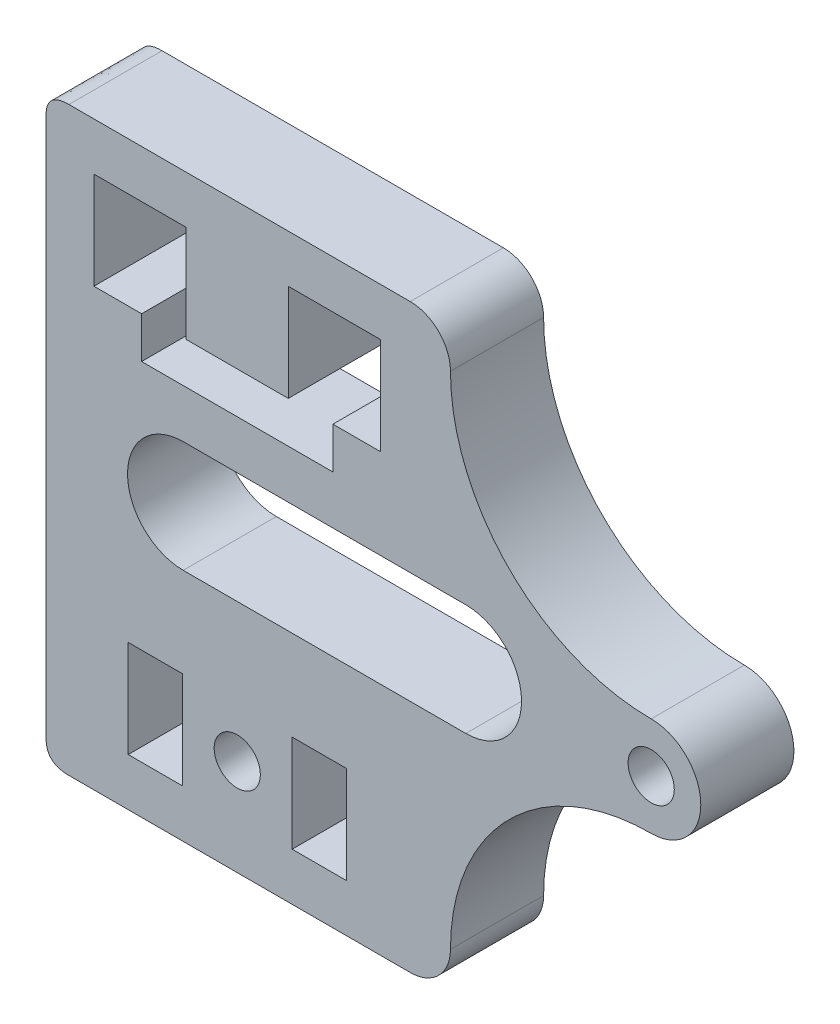
SolidWorks part; units mm, degrees
material "Acrylic (Medium-high impact)"
ref_plane "Front Plane" through (0, 0, 0) normal (0, 0, 1) x (1, 0, 0)
ref_plane "Top Plane" through (0, 0, 0) normal (0, 1, 0) x (1, 0, 0)
ref_plane "Right Plane" through (0, 0, 0) normal (1, 0, 0) x (0, 0, -1)
sketch "Sketch1" plane through (0, 0, 0) normal (0, 0, 1) x (1, 0, 0)
  line L0 (405.5669, 551.1889) -> (405.5669, 553.7889)
  line L1 (396.3551, 553.7889) -> (402.763, 553.7889)
  line L2 (393.5512, 553.7889) -> (393.5512, 551.1889)
  line L3 (393.5512, 551.1889) -> (405.5669, 551.1889)
  line L4 (390.5551, 559.8889) -> (390.5551, 553.7889)
  line L5 (393.5512, 553.7889) -> (390.5551, 553.7889)
  line L6 (396.3551, 559.8889) -> (390.5551, 559.8889)
  line L7 (396.3551, 553.7889) -> (396.3551, 559.8889)
  line L8 (405.5669, 553.7889) -> (408.563, 553.7889)
  line L9 (408.563, 553.7889) -> (408.563, 559.8889)
  line L10 (402.763, 559.8889) -> (402.763, 553.7889)
  line L11 (408.563, 559.8889) -> (402.763, 559.8889)
  line L12 (392.709, 535.4889) -> (392.709, 529.3889)
  line L13 (392.709, 529.3889) -> (396.109, 529.3889)
  line L14 (396.109, 535.4889) -> (392.709, 535.4889)
  line L15 (396.109, 529.3889) -> (396.109, 535.4889)
  line L16 (403.009, 529.3889) -> (406.4091, 529.3889)
  line L17 (406.4091, 529.3889) -> (406.4091, 535.4889)
  line L18 (403.009, 535.4889) -> (403.009, 529.3889)
  line L19 (406.4091, 535.4889) -> (403.009, 535.4889)
  line L20 (388.9846, 562.8889) -> (410.4246, 562.8889)
  line L21 (387.5551, 561.4608) -> (387.5551, 527.817)
  line L22 (388.9846, 526.3889) -> (410.4246, 526.3889)
  line L23 (-605.591, 535.4889) -> (49394.409, 535.4889) construction
  line L24 (396.1657, 548.1389) -> (413.9157, 548.1389)
  line L25 (396.1657, 541.1389) -> (413.9157, 541.1389)
  line L26 (-600.441, 544.6389) -> (49399.559, 544.6389) construction
  line L27 (398.109, 532.4389) -> (396.109, 532.4389) construction
  line L28 (401.009, 532.4389) -> (403.009, 532.4389) construction
  line L29 (399.559, -466.6171) -> (399.559, 49533.3829) construction
  line L30 (425.559, -455.7473) -> (425.559, 49544.2527) construction
  line L31 (-608.8734, 553.7889) -> (49391.1266, 553.7889) construction
  line L32 (421.909, 544.6389) -> (421.909, 535.4889) construction
  line L33 (421.909, 544.6389) -> (421.909, 553.7889) construction
  line L34 (412.9514, 560.3621) -> (412.9514, 528.9157) construction
  circle A0 centre (425.559, 544.6389) radius 1.45
  arc A1 (396.1657, 548.1389) -> (396.1657, 541.1389) centre (396.1657, 544.6389) ccw
  circle A2 centre (399.559, 532.4389) radius 1.45
  arc A3 (412.9514, 528.9157) -> (425.559, 541.5233) centre (425.559, 528.9157) cw
  arc A4 (412.9514, 560.3621) -> (425.559, 547.7545) centre (425.559, 560.3621) ccw
  arc A5 (425.559, 547.7545) -> (425.559, 541.5233) centre (425.559, 544.6389) cw
  arc A7 (413.9157, 548.1389) -> (413.9157, 541.1389) centre (413.9157, 544.6389) cw
  arc A8 (410.4246, 526.3889) -> (412.9514, 528.9157) centre (410.4246, 528.9157) ccw
  arc A9 (410.4246, 562.8889) -> (412.9514, 560.3621) centre (410.4246, 560.3621) cw
  spline S36 degree 2 poles (387.5551, 561.4608) (387.4764, 562.8889) (388.9846, 562.8889) knots 0 0 0 1 1 1
  spline S37 degree 2 poles (387.5551, 527.817) (387.4764, 526.3889) (388.9846, 526.3889) knots 0 0 0 1 1 1
  point P26 (399.559, 544.6389)
  point P30 (399.559, 553.7889)
  point P38 (394.409, 535.4889)
  point P40 (412.9514, 544.6389)
  dimension "D5" = 2.9
  dimension "D12" = 6.1
  dimension "D18" = 6.4078
  dimension "D16" = 3.5
  dimension "D2" = 3.4
  dimension "D3" = 5.8
  dimension "D4" = 2.6
  dimension "D6" = 2
  dimension "D7" = 18.3
  dimension "D8" = 3
  dimension "D9" = 3
  dimension "D10" = 3
  dimension "D11" = 26
  dimension "D13" = 12.0157
  dimension "D14" = 36.5
  dimension "D15" = 31.4465
  dimension "D17" = 17.75
  dimension "D19" = 13.3924
  dimension "D20" = 22.35
  dimension "D21" = 7
extrude "Boss-Extrude2" add sketch "Sketch1" along normal blind 5.85
sketch "Sketch2" plane through (0, 0, 0) normal (0, 0, 1) x (1, 0, 0)
  line L0 (-600.441, 532.4389) -> (49399.559, 532.4389) construction
  line L1 (406.4091, 529.3889) -> (406.4091, 535.4889) construction
  circle A0 centre (409.6591, 532.4389) radius 1.25
  point P5 (408.4091, 532.4389)
  dimension "D1" = 2.5
  dimension "D2" = 2
extrude "Cut-Extrude1" cut sketch "Sketch2" along normal blind 1
